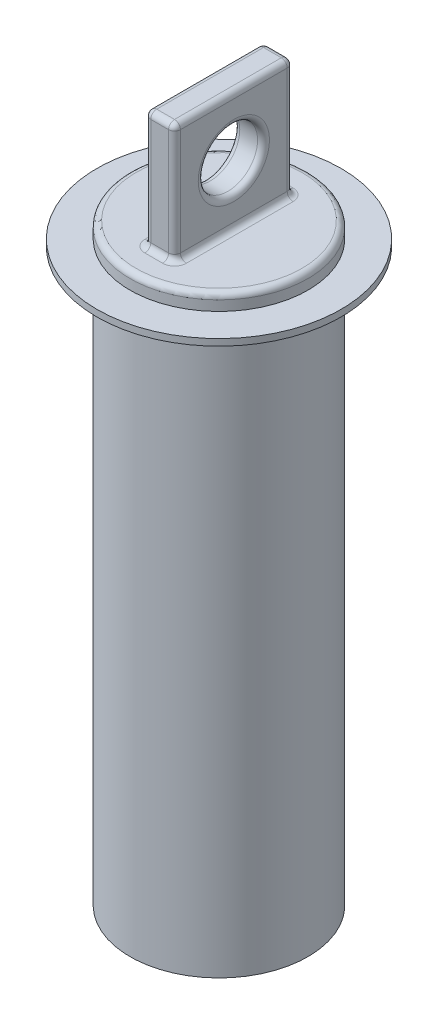
SolidWorks part; units mm, degrees
ref_plane "Front Plane" through (0, 0, 0) normal (0, 0, 1) x (1, 0, 0)
ref_plane "Top Plane" through (0, 0, 0) normal (0, 1, 0) x (1, 0, 0)
ref_plane "Right Plane" through (0, 0, 0) normal (1, 0, 0) x (0, 0, -1)
sketch "Sketch1" plane through (0, 0, 0) normal (1, 0, 0) x (0, 0, -1)
  line L4 (-15, 40) -> (-15, -60)
  line L5 (-15, -60) -> (-13, -60)
  line L6 (0, 38) -> (0, 40)
  line L7 (0, 40) -> (-15, 40)
  line L8 (0, 38) -> (-13, 38)
  line L9 (-13, 38) -> (-13, -60)
  line L10 (0, 0) -> (0, 40) construction
  dimension "D1" = 15
  dimension "D2" = 100
  dimension "D3" = 2
  dimension "D4" = 2
revolve "Revolve1" add sketch "Sketch1" angle 360 about L10
sketch "Sketch2" plane through (0, 40, 0) normal (0, 1, 0) x (1, 0, 0)
  line L1 (2.5, -10) -> (-2.5, -10)
  line L2 (2.5, -10) -> (2.5, 10)
  line L3 (2.5, 10) -> (-2.5, 10)
  line L4 (-2.5, -10) -> (-2.5, 10)
  line L5 (2.5, -10) -> (-2.5, 10) construction
  line L6 (2.5, 10) -> (-2.5, -10) construction
  point P0 (0, 0)
  dimension "D1" = 5
  dimension "D2" = 20
extrude "Boss-Extrude1" add sketch "Sketch2" along normal blind 20
sketch "Sketch3" plane through (2.5, 0, 0) normal (1, 0, 0) x (0, 0, -1)
  line L0 (10, 50) -> (-10, 50) construction
  line L1 (10, 60) -> (10, 40) construction
  line L2 (-10, 60) -> (-10, 40) construction
  circle A0 centre (0, 50) radius 5
extrude "Cut-Extrude1" cut sketch "Sketch3" against normal through all both and the other way through all
fillet "Fillet2" radius 1 16 edges at (0, 40, -15) (0, 38, -13) (-2.5, 50, 10) (2.5, 50, 10) (2.5, 50, -10) (-2.5, 50, -10) (0, 60, -10) (2.5, 60, 0) (0, 60, 10) (-2.5, 60, 0) (0, 40, -10) (2.5, 40, 0) (0, 40, 10) (-2.5, 40, 0) (-2.5, 50, -5) (2.5, 50, 5)
sketch "Sketch4" plane through (0, 0, 0) normal (0, 0, 1) x (1, 0, 0)
  line L0 (15, -60) -> (15, 39) construction
  line L1 (15, 37.3091) -> (20.5863, 37.3091)
  line L2 (15, 37.3091) -> (15, 36.1912)
  line L3 (15, 36.1912) -> (20.5863, 36.1912)
  line L4 (20.5863, 37.3091) -> (20.5863, 36.1912)
revolve "Revolve2" add sketch "Sketch4" angle 360 about L10
